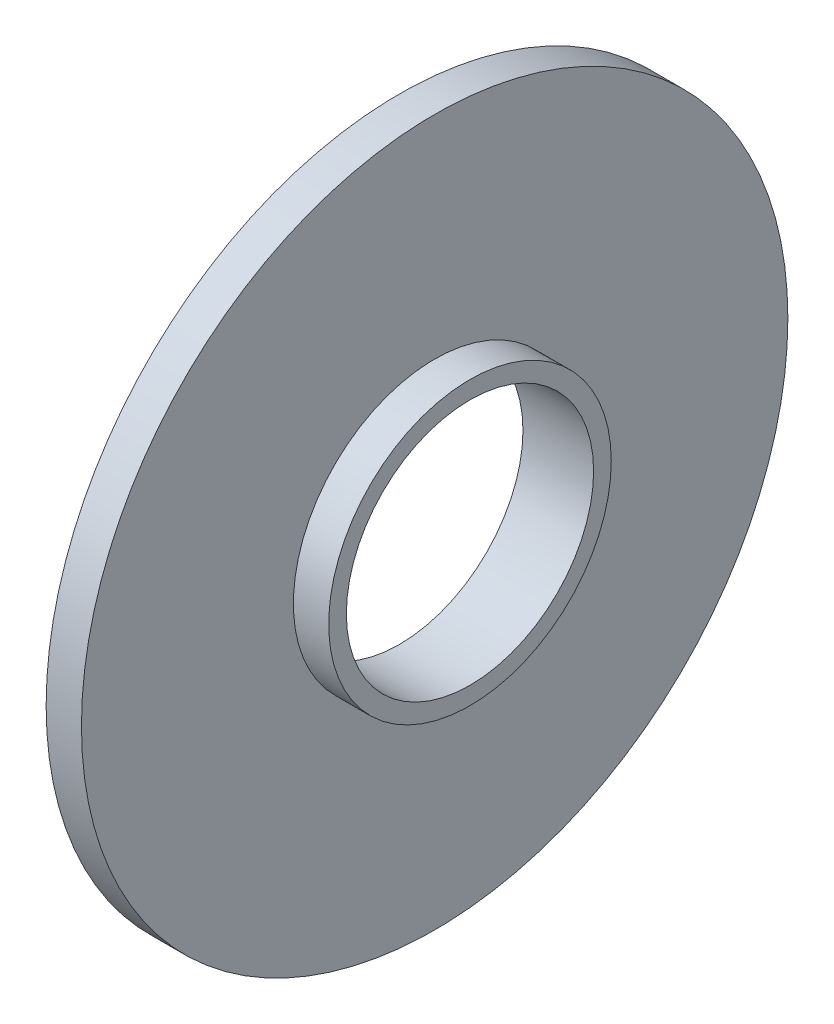
SolidWorks part; units mm, degrees
ref_plane "Front Plane" through (0, 0, 0) normal (0, 0, 1) x (1, 0, 0)
ref_plane "Top Plane" through (0, 0, 0) normal (0, 1, 0) x (1, 0, 0)
ref_plane "Right Plane" through (0, 0, 0) normal (1, 0, 0) x (0, 0, -1)
sketch "Sketch1" plane through (0, 0, 0) normal (1, 0, 0) x (0, 0, -1)
  circle A0 centre (0, 0) radius 10
  circle A1 centre (0, 0) radius 3.5
  dimension "D1" = 20
  dimension "D2" = 7
extrude "Boss-Extrude1" add sketch "Sketch1" along normal blind 1
sketch "Sketch2" plane through (1, 0, 0) normal (1, 0, 0) x (0, 0, -1)
  circle A0 centre (0, 0) radius 3.5
  circle A1 centre (0, 0) radius 4
  dimension "D1" = 8
extrude "Boss-Extrude2" add sketch "Sketch2" along normal blind 1
